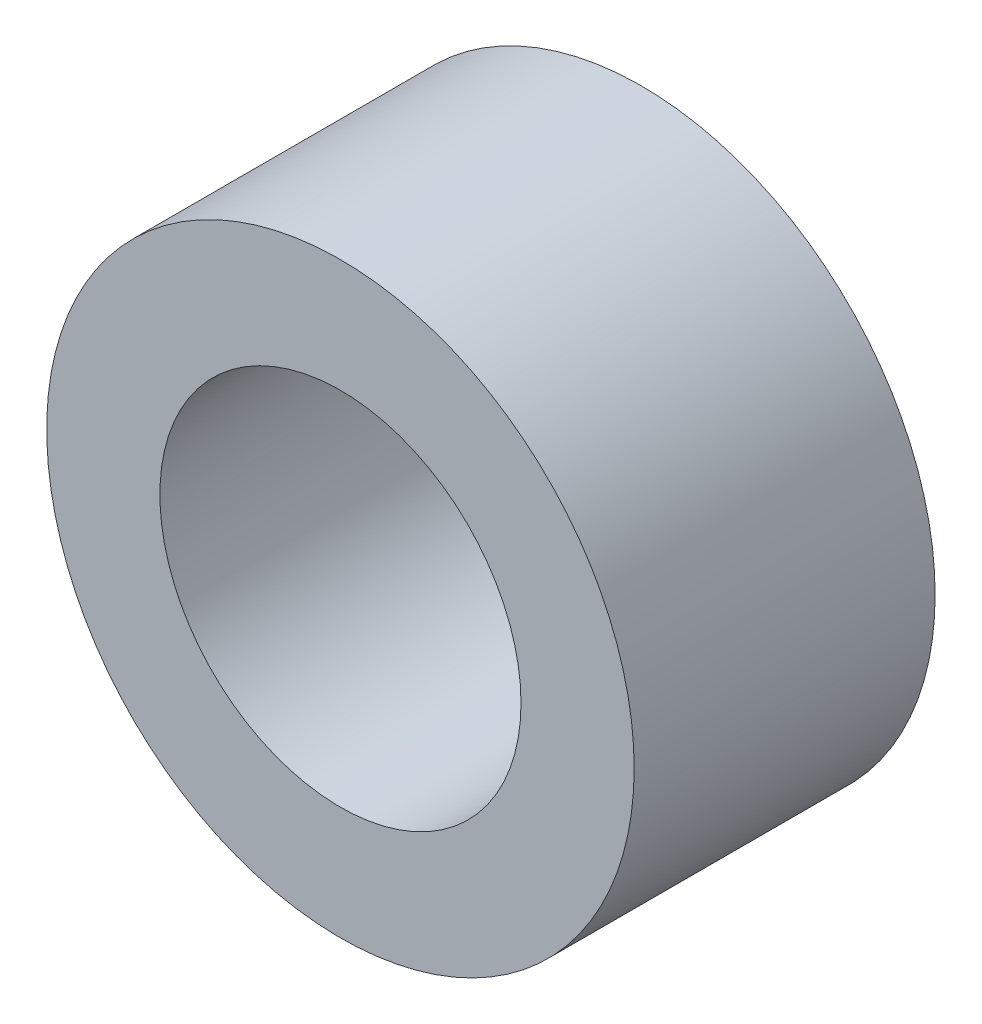
SolidWorks part; units mm, degrees
ref_plane "Front Plane" through (0, 0, 0) normal (0, 0, 1) x (1, 0, 0)
ref_plane "Top Plane" through (0, 0, 0) normal (0, 1, 0) x (1, 0, 0)
ref_plane "Right Plane" through (0, 0, 0) normal (1, 0, 0) x (0, 0, -1)
sketch "Sketch1" plane through (0, 0, 0) normal (0, 0, 1) x (1, 0, 0)
  circle A0 centre (0, 0) radius 3
  circle A1 centre (0, 0) radius 4.8805
  dimension "D1" = 6
extrude "Boss-Extrude1" add sketch "Sketch1" along normal blind 5
